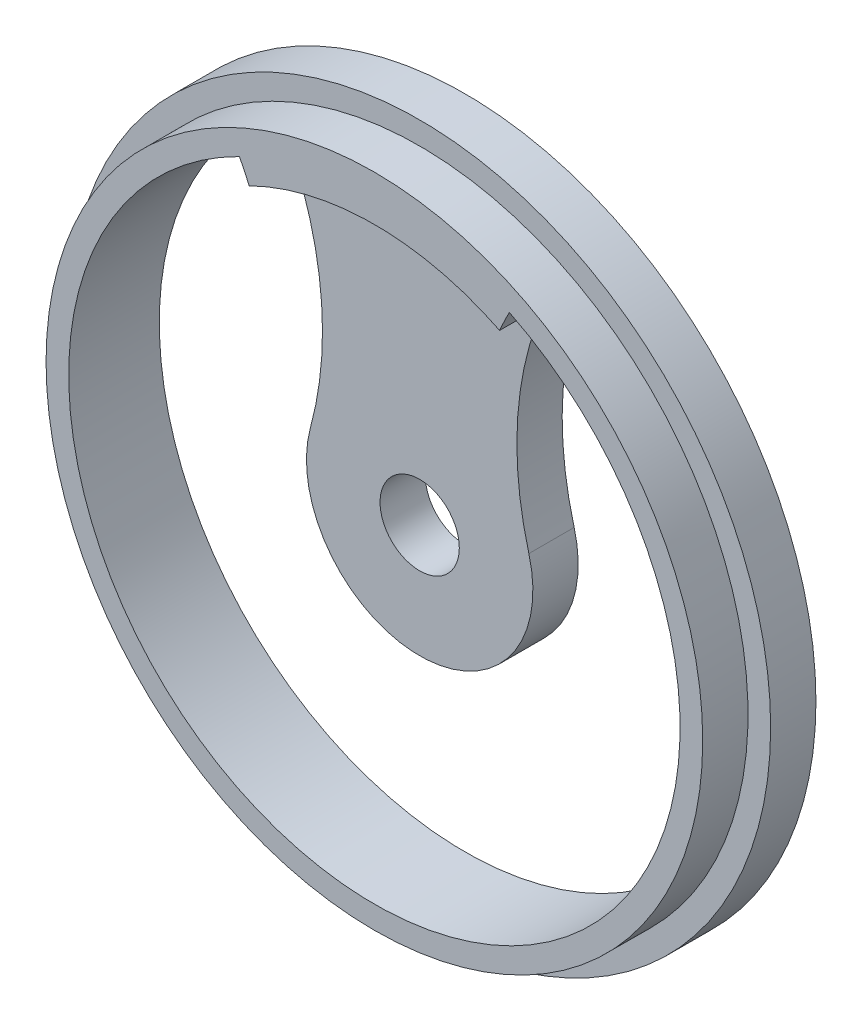
SolidWorks part; units mm, degrees
ref_plane "Front Plane" through (0, 0, 0) normal (0, 0, 1) x (1, 0, 0)
ref_plane "Top Plane" through (0, 0, 0) normal (0, 1, 0) x (1, 0, 0)
ref_plane "Right Plane" through (0, 0, 0) normal (1, 0, 0) x (0, 0, -1)
sketch "Sketch1" plane through (0, 0, 0) normal (0, 0, 1) x (1, 0, 0)
  circle A0 centre (0, 0) radius 14.5
  dimension "D1" = 29
extrude "Boss-Extrude1" add sketch "Sketch1" along normal blind 2
sketch "Sketch2" plane through (0, 0, 2) normal (0, 0, 1) x (1, 0, 0)
  circle A0 centre (0, 0) radius 14.5 construction
  circle A1 centre (0, 0) radius 14.5
  circle A2 centre (0, 0) radius 12.5
  dimension "D1" = 2
extrude "Boss-Extrude2" add sketch "Sketch2" along normal blind 2
sketch "Sketch3" plane through (0, 0, 2) normal (0, 0, 1) x (1, 0, 0)
  circle A0 centre (0, 0) radius 1.75
  dimension "D1" = 3.5
extrude "Cut-Extrude1" cut sketch "Sketch3" against normal blind 2
sketch "Sketch4" plane through (0, 0, 0) normal (0, 0, -1) x (-1, 0, 0)
  circle A0 centre (0, 0) radius 14.5 construction
  circle A1 centre (0, 0) radius 14.5
  circle A2 centre (0, 0) radius 15.5
  dimension "D1" = 1
extrude "Boss-Extrude3" add sketch "Sketch4" against normal blind 2
sketch "Sketch5" plane through (0, 0, 0) normal (0, 0, -1) x (-1, 0, 0)
  line L0 (0, 0) -> (0, 18.6095) construction
  arc A2 (-4.8223, 1.3212) -> (4.8223, 1.3212) centre (0, 0) ccw
  arc A3 (-4.8223, 1.3212) -> (-5.96, 12.1131) centre (-19.2032, 5.2611) ccw
  arc A4 (4.8223, 1.3212) -> (5.96, 12.1131) centre (19.2032, 5.2611) cw
  arc A5 (-5.96, 12.1131) -> (5.96, 12.1131) centre (0, 0) ccw
  point P13 (14.8227, 4.5318)
  dimension "D1" = 10
extrude "Cut-Extrude2" cut sketch "Sketch5" against normal through all
